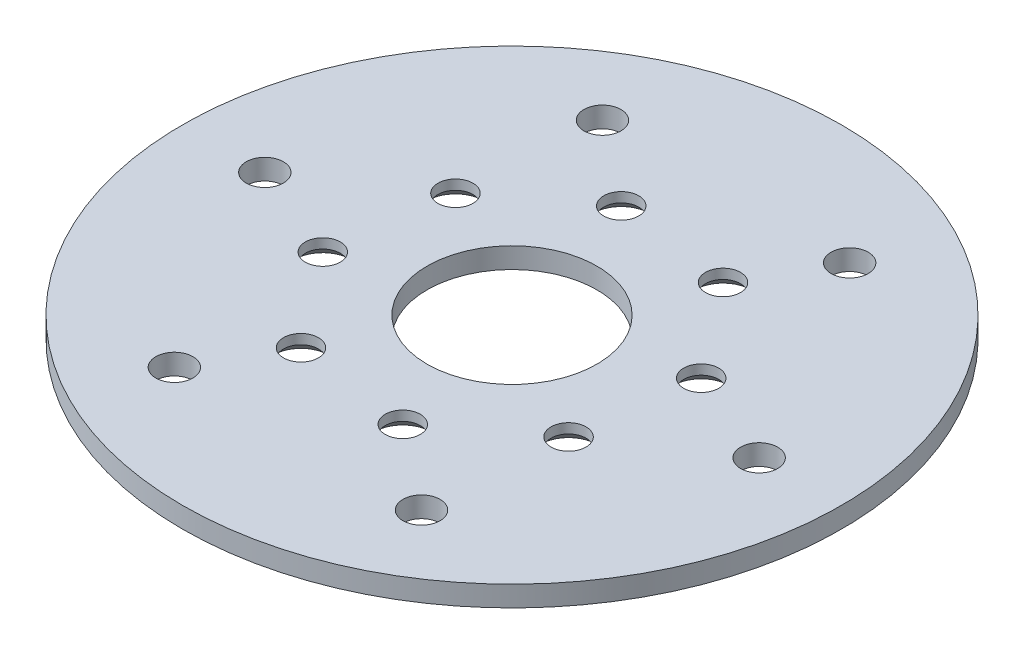
SolidWorks part; units mm, degrees
ref_plane "Front Plane" through (0, 0, 0) normal (0, 0, 1) x (1, 0, 0)
ref_plane "Top Plane" through (0, 0, 0) normal (0, 1, 0) x (1, 0, 0)
ref_plane "Right Plane" through (0, 0, 0) normal (1, 0, 0) x (0, 0, -1)
sketch "Sketch1" plane through (0, 0, 0) normal (0, 1, 0) x (1, 0, 0)
  circle A0 centre (0, 0) radius 8.25
  circle A1 centre (0, 0) radius 32
  dimension "D1" = 16.5
  dimension "D2" = 64
extrude "Boss-Extrude1" add sketch "Sketch1" along normal blind 2
sketch "Sketch2" plane through (0, 2, 0) normal (0, 1, 0) x (1, 0, 0)
  circle A0 centre (0, 21) radius 4
  circle A1 centre (0, 0) radius 21 construction
  circle A2 centre (18.1865, 10.5) radius 4
  circle A3 centre (18.1865, -10.5) radius 4
  circle A4 centre (0, -21) radius 4
  circle A5 centre (-18.1865, -10.5) radius 4
  circle A6 centre (-18.1865, 10.5) radius 4
  point P17 (0, 0)
  dimension "D1" = 8
  dimension "D2" = 42
  dimension "D3" = 6
extrude "Cut-Extrude1" [suppressed] cut sketch "Sketch2" against normal through all and the other way through all
hole_wizard "CSK for M3 Hex Socket Countersunk Head Screw1" positions "Sketch3" profile "Sketch4" countersink size "M3" standard "DIN" end condition up to next
sketch "Sketch3" plane through (0, 0, 0) normal (0, 1, 0) x (1, 0, 0)
  line L0 (0, 0) -> (18.891, 32.7202) construction
  circle A0 centre (0, 0) radius 15
  point P8 (7.5, 12.9904)
  point P14 (14.4889, 3.8823)
  point P15 (12.9904, -7.5)
  point P16 (3.8823, -14.4889)
  point P17 (-7.5, -12.9904)
  point P18 (-14.4889, -3.8823)
  point P19 (-12.9904, 7.5)
  point P20 (-3.8823, 14.4889)
  dimension "D2" = 30
  dimension "D1" = 60
  dimension "D3" = 8
sketch "Sketch4" plane through (-3.8823, 0, -14.4889) normal (1, 0, 0) x (0, 0, -1)
  line L0 (0, 0) -> (0, 2)
  line L1 (0, 2) -> (1.7, 2)
  line L2 (1.7, 2) -> (1.7, 1.05)
  line L3 (1.7, 1.05) -> (2.75, 0)
  line L5 (2.75, 0) -> (0, 0)
  line L6 (-1.7, 1.05) -> (-2.75, 0) construction
  line L11 (0, -6.35) -> (0, 107.95) construction
  dimension "Thru Hole Dia." = 3.4
  dimension "Thru Hole Depth" = 2
  dimension "Near C'Sink Dia." = 5.5
  dimension "Near C'Sink Angle" = 90
hole_wizard "M3 Clearance Hole1" positions "Sketch5" profile "Sketch7" hole size "M3" standard "DIN" end condition up to next
sketch "Sketch5" plane through (0, 0, 0) normal (0, -1, 0) x (-1, 0, 0)
  circle A0 centre (0, 0) radius 24
  point P6 (-24, 0)
  point P14 (-12, 20.7846)
  point P15 (12, 20.7846)
  point P16 (24, 0)
  point P17 (12, -20.7846)
  point P18 (-12, -20.7846)
  dimension "D1" = 48
sketch "Sketch7" plane through (12, 0, 20.7846) normal (1, 0, 0) x (0, 0, -1)
  line L0 (0, 0) -> (0, 2)
  line L1 (0, 2) -> (1.8, 2)
  line L2 (1.8, 2) -> (1.8, 0)
  line L5 (1.8, 0) -> (0, 0)
  line L11 (0, -6.35) -> (0, 107.95) construction
  dimension "Thru Hole Dia." = 3.6
  dimension "Thru Hole Depth" = 2
hole_wizard "Ø3.2 (3.2) Diameter Hole1" [suppressed] positions "Sketch8" profile "Sketch9" hole size "Ø3.2" standard "DIN"
sketch "Sketch8" plane through (0, 0, 0) normal (0, -1, 0) x (-1, 0, 0)
  circle A0 centre (0, 0) radius 15
  point P5 (0, 15)
  point P12 (12.9904, 7.5)
  point P13 (12.9904, -7.5)
  point P14 (0, -15)
  point P15 (-12.9904, -7.5)
  point P16 (-12.9904, 7.5)
  dimension "D1" = 30
  dimension "D2" = 6
sketch "Sketch9" plane through (12.9904, 0, -7.5) normal (1, 0, 0) x (0, 0, -1)
  line L0 (0, 0) -> (0, 2)
  line L1 (0, 2) -> (1.6, 2)
  line L2 (1.6, 2) -> (1.6, 0)
  line L5 (1.6, 0) -> (0, 0)
  line L11 (0, -6.35) -> (0, 107.95) construction
  dimension "Thru Hole Dia." = 3.2
  dimension "Thru Hole Depth" = 2
